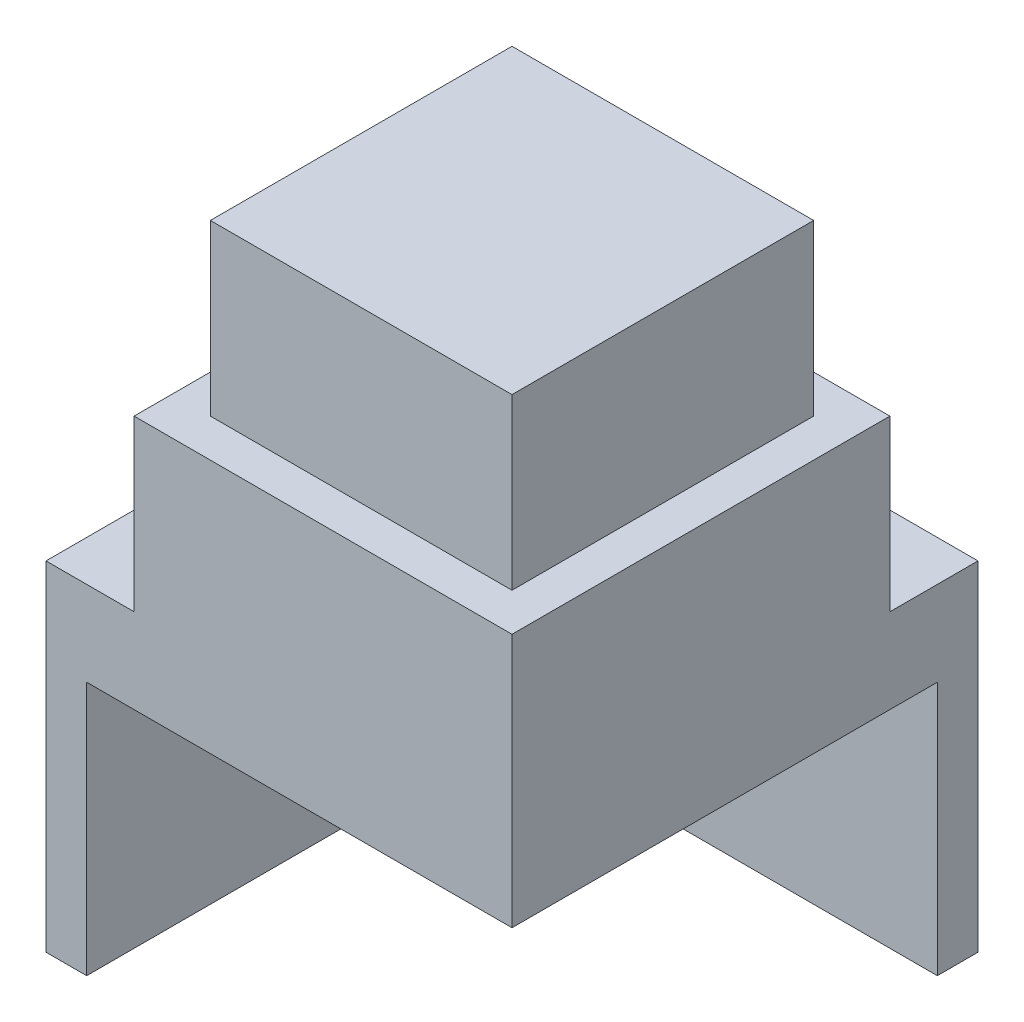
SolidWorks part; units mm, degrees
ref_plane "Front Plane" through (0, 0, 0) normal (0, 0, 1) x (1, 0, 0)
ref_plane "Top Plane" through (0, 0, 0) normal (0, 1, 0) x (1, 0, 0)
ref_plane "Right Plane" through (0, 0, 0) normal (1, 0, 0) x (0, 0, -1)
sketch "Sketch1" plane through (0, 0, 0) normal (0, 1, 0) x (1, 0, 0)
  line L1 (-13.75, 13.75) -> (13.75, 13.75)
  line L2 (-13.75, 13.75) -> (-13.75, -13.75)
  line L3 (-13.75, -13.75) -> (13.75, -13.75)
  line L4 (13.75, 13.75) -> (13.75, -13.75)
  line L5 (-13.75, 13.75) -> (13.75, -13.75) construction
  line L6 (-13.75, -13.75) -> (13.75, 13.75) construction
  point P0 (0, 0)
  dimension "D1" = 27.5
  dimension "D2" = 27.5
extrude "Boss-Extrude3" add sketch "Sketch1" along normal blind 15
sketch "Sketch3" plane through (0, 15, 0) normal (0, 1, 0) x (1, 0, 0)
  line L1 (13.75, -13.75) -> (-8.55, -13.75)
  line L2 (13.75, -13.75) -> (13.75, 8.55)
  line L3 (13.75, 8.55) -> (-8.55, 8.55)
  line L4 (-8.55, -13.75) -> (-8.55, 8.55)
  line L5 (13.75, -13.75) -> (-13.75, -13.75)
  line L6 (13.75, -13.75) -> (13.75, 13.75)
  line L7 (13.75, 13.75) -> (-13.75, 13.75)
  line L8 (-13.75, -13.75) -> (-13.75, 13.75)
  line M3 (13.75, -13.75) -> (13.75, 13.75)
  line M4 (13.75, 13.75) -> (-13.75, 13.75)
  line M5 (-13.75, 13.75) -> (-13.75, -13.75)
  line M6 (-13.75, -13.75) -> (13.75, -13.75)
  dimension "D1" = 22.3
  dimension "D2" = 22.3
extrude "Cut-Extrude1" cut sketch "Sketch3" against normal blind 10 contours L4 L3 M6 M3 M4 M5
sketch "Sketch4" plane through (0, 15, 0) normal (0, 1, 0) x (1, 0, 0)
  line L0 (2.6, 8.55) -> (2.6, -13.75) construction
  line L1 (13.75, 8.55) -> (-8.55, 8.55) construction
  line L2 (-8.55, -13.75) -> (13.75, -13.75) construction
  line L4 (-6.3, 6.3) -> (11.5, 6.3)
  line L5 (-6.3, 6.3) -> (-6.3, -11.5)
  line L6 (-6.3, -11.5) -> (11.5, -11.5)
  line L7 (11.5, 6.3) -> (11.5, -11.5)
  line L8 (-6.3, 6.3) -> (11.5, -11.5) construction
  line L9 (-6.3, -11.5) -> (11.5, 6.3) construction
  point P6 (2.6, -2.6)
  dimension "D1" = 17.8
  dimension "D2" = 17.8
extrude "Boss-Extrude4" add sketch "Sketch4" along normal blind 10
sketch "Sketch6" plane through (0, 0, 0) normal (0, -1, 0) x (1, 0, 0)
  line L1 (13.75, 13.75) -> (-11.35, 13.75)
  line L2 (13.75, 13.75) -> (13.75, -11.35)
  line L3 (13.75, -11.35) -> (-11.35, -11.35)
  line L4 (-11.35, 13.75) -> (-11.35, -11.35)
  line L5 (13.75, 13.75) -> (-13.75, 13.75)
  line L6 (13.75, 13.75) -> (13.75, -13.75)
  line L7 (13.75, -13.75) -> (-13.75, -13.75)
  line L8 (-13.75, 13.75) -> (-13.75, -13.75)
  line M9 (13.75, -13.75) -> (13.75, 13.75)
  line M10 (13.75, 13.75) -> (-13.75, 13.75)
  line M11 (-13.75, 13.75) -> (-13.75, -13.75)
  line M12 (-13.75, -13.75) -> (13.75, -13.75)
  dimension "D1" = 25.1
  dimension "D2" = 25.1
extrude "Boss-Extrude5" add sketch "Sketch6" along normal blind 15 contours L4 L3 M10 M11 M12 M9
